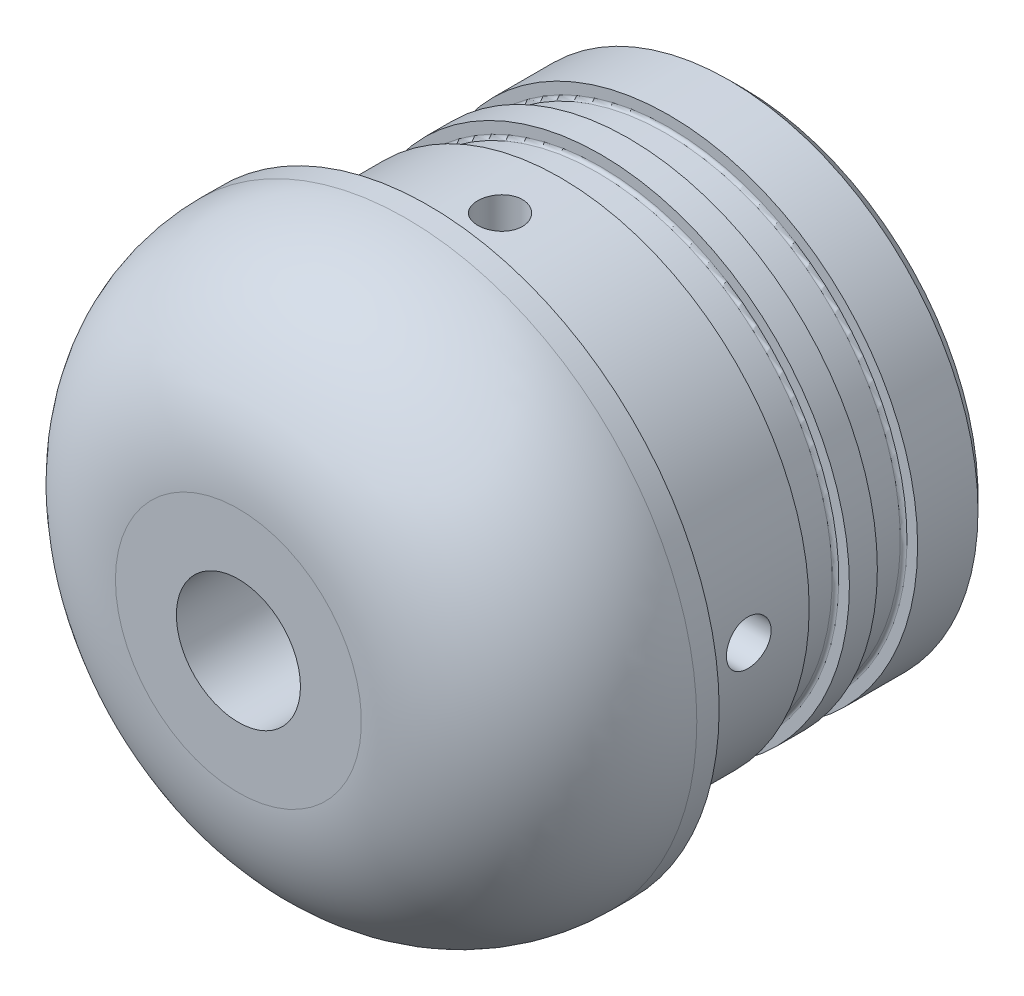
SolidWorks part; units mm, degrees
material "6061-T6 (SS)"
ref_plane "Front Plane" through (0, 0, 0) normal (0, 0, 1) x (1, 0, 0)
ref_plane "Top Plane" through (0, 0, 0) normal (0, 1, 0) x (1, 0, 0)
ref_plane "Right Plane" through (0, 0, 0) normal (1, 0, 0) x (0, 0, -1)
sketch "Sketch1" plane through (0, 0, 0) normal (1, 0, 0) x (0, 0, -1)
  line L0 (-36.3161, 0) -> (36.3161, 0) construction
  line L1 (-28.1, 16.2314) -> (-28.1, 22.25)
  line L2 (-28.1, 22.25) -> (-16.3, 22.25)
  line L3 (-16.3, 22.25) -> (-16.3, 21)
  line L4 (-16.3, 21) -> (-12.7, 21)
  line L5 (-12.7, 21) -> (-12.7, 22.25)
  line L6 (-12.7, 22.25) -> (-10.2, 22.25)
  line L7 (-10.2, 22.25) -> (-10.2, 21)
  line L8 (-10.2, 21) -> (-6.6, 21)
  line L9 (-6.6, 21) -> (-6.6, 22.25)
  line L10 (-6.6, 22.25) -> (-1.2, 22.25)
  line L11 (-1.2, 22.25) -> (0, 21.05)
  line L12 (0, 21.05) -> (0, 12.25)
  line L13 (0, 12.25) -> (-28.1, 12.25)
  line L14 (-28.1, 12.25) -> (-28.1, 16.2314)
  point P3 (0, 0)
  dimension "D1" = 21
  dimension "D2" = 2.5
  dimension "D3" = 3.6
  dimension "D4" = 22.25
  dimension "D5" = 10
  dimension "D6" = 45
  dimension "D7" = 26.9
  dimension "D8" = 1.2
  dimension "D9" = 11.8
revolve "Revolve1" add sketch "Sketch1" angle 360 about L0
sketch "Sketch3" plane through (0, 0, 28.1) normal (0, 0, 1) x (1, 0, 0)
  circle A0 centre (0, 0) radius 22.25 construction
  circle A1 centre (0, 0) radius 22.25 construction
  circle A2 centre (0, 0) radius 26
  circle A3 centre (0, 0) radius 12.25 construction
  circle A4 centre (0, 0) radius 12.25
  dimension "D1" = 52
extrude "Boss-Extrude1" add sketch "Sketch3" along normal blind 2
sketch "Sketch4" plane through (0, 0, 0) normal (0, 1, 0) x (1, 0, 0)
  line L0 (0, -30.1) -> (0, -45.1)
  line L1 (0, 0) -> (0, -30.1) construction
  line L2 (-26, -30.1) -> (0, -30.1)
  line L4 (-11, -45.1) -> (0, -45.1)
  line L5 (-26, -28.1) -> (-26, -30.1) construction
  arc A2 (-26, -30.1) -> (-11, -45.1) centre (-11, -30.1) ccw
  dimension "D2" = 15
revolve "Revolve9" add sketch "Sketch4" angle 360 about L1
sketch "Sketch11" plane through (0, 0, 30.1) normal (0, 0, -1) x (-1, 0, 0)
  circle A1 centre (0, 0) radius 12.25
  circle A2 centre (0, 0) radius 12.25
  dimension "D1" = 0
extrude "Boss-Extrude2" add sketch "Sketch11" along normal blind 13
sketch "Sketch12" plane through (0, 0, 45.1) normal (0, 0, 1) x (1, 0, 0)
  circle A0 centre (0, 0) radius 5.55
  dimension "D1" = 11.1
extrude "Cut-Extrude7" cut sketch "Sketch12" against normal up to surface (28 mm away) up to face at (-12.25, 0, 17.1)
cosmetic thread "Cosmetic Thread1" parameters "D2"=12.1
ref_plane "Plane1" through (22.25, 0, 0) normal (1, 0, 0) x (0, 0, -1)
sketch "Sketch6" plane through (22.25, 0, 0) normal (1, 0, 0) x (0, 0, -1)
  line L0 (0, 0) -> (-56.3225, 0) construction
  line L9 (-16.3, -22.25) -> (-16.3, 22.25) construction
  circle A0 centre (-21.7, 0) radius 2
  dimension "D1" = 4
  dimension "D2" = 5.4
extrude "Cut-Extrude4" cut sketch "Sketch6" against normal blind 6
cosmetic thread "Cosmetic Thread3" parameters "D2"=4.7
cosmetic thread "Cosmetic Thread12" parameters "D2"=4.7
sketch "Sketch9" plane through (0, 0, 0) normal (0, 0, -1) x (-1, 0, 0)
  circle A0 centre (0, 0) radius 16.5
  dimension "D1" = 33
extrude "Cut-Extrude6" cut sketch "Sketch9" against normal up to surface (17.1 mm away) up to face at (-5.55, 0, 17.1)
chamfer "Chamfer1" distance 4 angle 45 2 edges at (-5.55, 0, 17.1) (-16.5, 0, 17.1)
fillet "Fillet1" radius 0.3 4 edges at (0, -21, 12.7) (0, -21, 16.3) (0, -21, 10.2) (0, -21, 6.6)
pattern_circular "CirPattern1" count 4 over 360 about axis through (0, 0, 0) along (0, 0, 1) of "Cut-Extrude4"
cosmetic thread "Cosmetic Thread2" parameters "D2"=4.7
cosmetic thread "Cosmetic Thread4" parameters "D2"=4.7
cosmetic thread "Cosmetic Thread5" parameters "D2"=4.7
cosmetic thread "Cosmetic Thread6" parameters "D2"=4.7
cosmetic thread "Cosmetic Thread7" parameters "D2"=4.7
cosmetic thread "Cosmetic Thread8" parameters "D2"=4.7
cosmetic thread "Cosmetic Thread10" parameters "D2"=4.7
cosmetic thread "Cosmetic Thread11" parameters "D2"=4.7
cosmetic thread "Cosmetic Thread13" parameters "D2"=4.7
cosmetic thread "Cosmetic Thread14" parameters "D2"=4.7
cosmetic thread "Cosmetic Thread15" parameters "D2"=4.7
cosmetic thread "Cosmetic Thread16" parameters "D2"=4.7
sketch "Sketch13" plane through (0, 0, 0) normal (0, 0, -1) x (-1, 0, 0)
  circle A0 centre (0, 0) radius 18
  dimension "D1" = 36
extrude "Cut-Extrude8" cut sketch "Sketch13" against normal up to surface (17.1 mm away) up to face at (-12.5, 0, 17.1)
chamfer "Chamfer3" distance 4 angle 45 1 edges at (-18, 0, 17.1)
ref_plane "Plane2" through (0, 0, 2.5) normal (0, 0, -1) x (-1, 0, 0)
sketch "Sketch14" plane through (0, 0, 2.5) normal (0, 0, -1) x (-1, 0, 0)
  circle A0 centre (0, 0) radius 19
  dimension "D1" = 38
extrude "Cut-Extrude9" cut sketch "Sketch14" against normal blind 1.6
